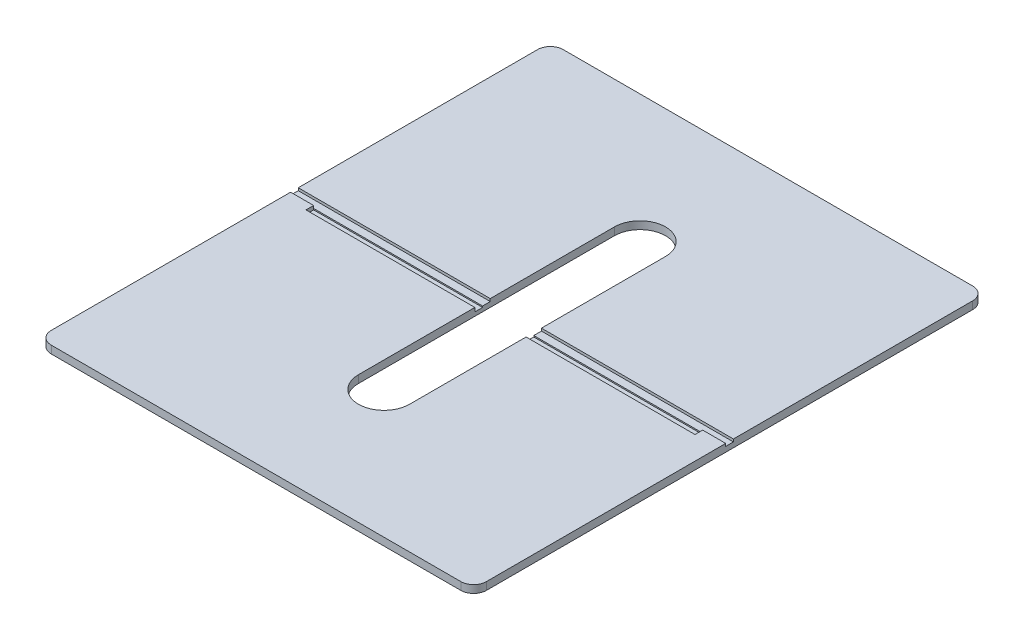
SolidWorks part; units mm, degrees
ref_plane "Спереди" through (0, 0, 0) normal (0, 0, 1) x (1, 0, 0)
ref_plane "Сверху" through (0, 0, 0) normal (0, 1, 0) x (1, 0, 0)
ref_plane "Справа" through (0, 0, 0) normal (1, 0, 0) x (0, 0, -1)
other "Configuration Table"
sketch "Эскиз1" plane through (0, 0, 0) normal (0, 1, 0) x (1, 0, 0)
  line L0 (0, 50) -> (0, -50) construction
  line L1 (-80, 100) -> (80, 100)
  line L2 (-85, 95) -> (-85, -95)
  line L3 (-80, -100) -> (80, -100)
  line L4 (85, 95) -> (85, -95)
  line L5 (-85, 100) -> (85, -100) construction
  line L6 (-85, -100) -> (85, 100) construction
  line L7 (10, 50) -> (10, -50)
  line L8 (-10, 50) -> (-10, -50)
  arc A0 (10, 50) -> (-10, 50) centre (0, 50) ccw
  arc A1 (-10, -50) -> (10, -50) centre (0, -50) ccw
  arc A4 (80, 100) -> (85, 95) centre (80, 95) cw
  arc A5 (85, -95) -> (80, -100) centre (80, -95) cw
  arc A6 (-80, -100) -> (-85, -95) centre (-80, -95) cw
  arc A7 (-80, 100) -> (-85, 95) centre (-80, 95) ccw
  point P0 (0, 0)
  point P8 (0, 0)
  dimension "D3" = 10
  dimension "D5" = 5
  dimension "D1" = 200
  dimension "D2" = 170
  dimension "D4" = 100
extrude "Бобышка-Вытянуть1" add sketch "Эскиз1" along normal mid plane 3
sketch "Эскиз3" plane through (0, 1.5, 0) normal (0, 1, 0) x (1, 0, 0)
  line L0 (-76, -1.5) -> (-76, -4.5)
  line L3 (-76, -3) -> (76, -3) construction
  line L4 (-76, -1.5) -> (76, -1.5)
  line L5 (-76, -4.5) -> (76, -4.5)
  line L6 (76, -1.5) -> (76, -4.5)
  line L7 (10, 50) -> (10, -50) construction
  line L8 (-80, 100) -> (80, 100) construction
  point P8 (0, -3)
  dimension "D1" = 3
  dimension "D2" = 1.5
  dimension "D3" = 152
  dimension "D4" = 66
  dimension "D5" = 101.5
  dimension "D6" = 103
extrude "Вырез-Вытянуть1" cut sketch "Эскиз3" against normal blind 1.5 and the other way through all
sketch "Эскиз4" plane through (0, 1.5, 0) normal (0, 1, 0) x (1, 0, 0)
  line L0 (88.2289, 0) -> (-88.2289, 0) construction
  line L1 (88.2289, -1.5) -> (-88.2289, -1.5)
  line L2 (88.2289, 1.5) -> (-88.2289, 1.5)
  arc A0 (88.2289, -1.5) -> (88.2289, 1.5) centre (88.2289, 0) ccw
  arc A1 (-88.2289, 1.5) -> (-88.2289, -1.5) centre (-88.2289, 0) ccw
  point P2 (0, 0)
  dimension "D1" = 1.5
extrude "Вырез-Вытянуть2" cut sketch "Эскиз4" against normal blind 1
